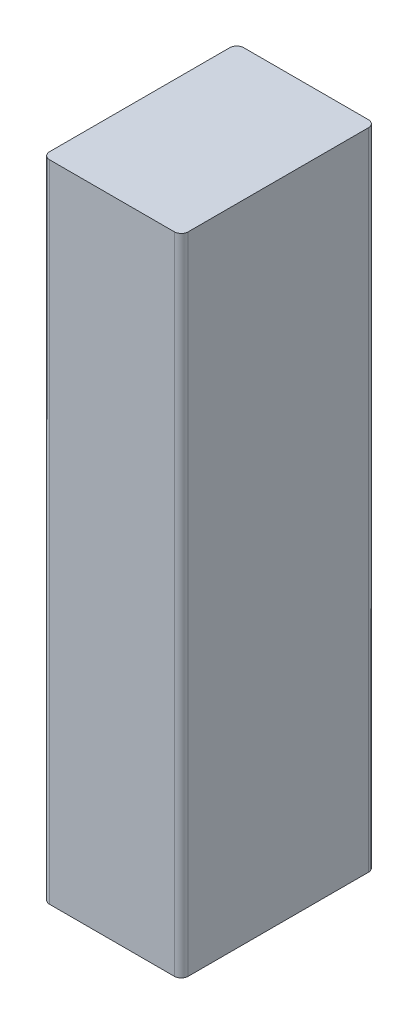
SolidWorks part; units mm, degrees
material "电源线路板"
ref_plane "前视基准面" through (0, 0, 0) normal (0, 0, 1) x (1, 0, 0)
ref_plane "上视基准面" through (0, 0, 0) normal (0, 1, 0) x (1, 0, 0)
ref_plane "右视基准面" through (0, 0, 0) normal (1, 0, 0) x (0, 0, -1)
other "Configuration Table"
sketch "草图1" plane through (0, 0, 0) normal (0, 1, 0) x (1, 0, 0)
  line L1 (32.105, 18.1049) -> (50.105, 18.1049)
  line L2 (31.105, 17.1049) -> (31.105, -8.8951)
  line L3 (32.105, -9.8951) -> (50.105, -9.8951)
  line L4 (51.105, 17.1049) -> (51.105, -8.8951)
  arc A0 (31.105, 17.1049) -> (32.105, 18.1049) centre (32.105, 17.1049) cw
  arc A1 (51.105, 17.1049) -> (50.105, 18.1049) centre (50.105, 17.1049) ccw
  arc A2 (50.105, -9.8951) -> (51.105, -8.8951) centre (50.105, -8.8951) ccw
  arc A3 (31.105, -8.8951) -> (32.105, -9.8951) centre (32.105, -8.8951) ccw
  point P6 (31.105, 18.1049)
  point P9 (51.105, 18.1049)
  point P12 (51.105, -9.8951)
  dimension "D3" = 1
  dimension "D4" = 1
  dimension "D5" = 1
  dimension "D6" = 1
  dimension "D1" = 20
  dimension "D2" = 28
extrude "凸台-拉伸2" add sketch "草图1" along normal blind 93
